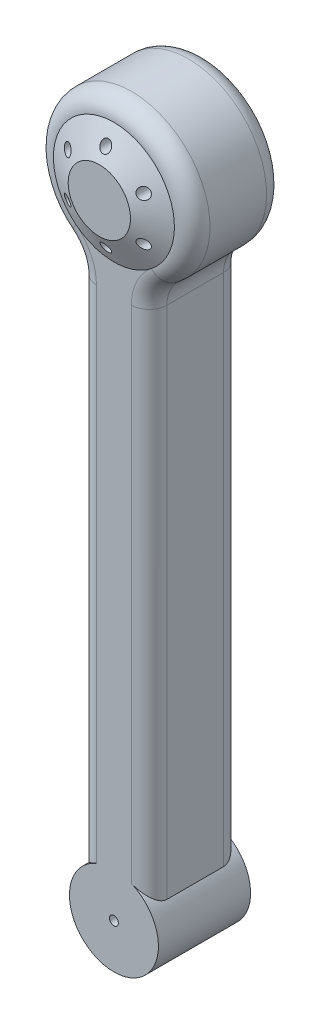
SolidWorks part; units mm, degrees
ref_plane "Ön Düzlem" through (0, 0, 0) normal (0, 0, 1) x (1, 0, 0)
ref_plane "Üst Düzlem" through (0, 0, 0) normal (0, 1, 0) x (1, 0, 0)
ref_plane "Sağ Düzlem" through (0, 0, 0) normal (1, 0, 0) x (0, 0, -1)
sketch "Çizim2" plane through (0, 0, 0) normal (0, 0, 1) x (1, 0, 0)
  line L2 (19.817, 315.2409) -> (19.817, 15.2409)
  line L3 (-19.817, 315.2409) -> (-19.817, 15.2409)
  arc A0 (-19.817, 15.2409) -> (19.817, 15.2409) centre (0, 0) ccw
  arc A1 (-19.817, 315.2409) -> (19.817, 315.2409) centre (0, 354.5256) cw
  point P3 (19.2221, 15.9847)
  point P6 (-19.2221, 15.9847)
  dimension "D1" = 50
  dimension "D4" = 44
  dimension "D2" = 300
  dimension "D3" = 300
extrude "Yükseklik-Ekstrüzyon2" add sketch "Çizim2" along normal blind 51.8
sketch "Çizim3" plane through (0, 0, 51.8) normal (0, 0, 1) x (1, 0, 0)
  circle A0 centre (0, 0) radius 2.5
  dimension "D1" = 5
extrude "Kes-Ekstrüzyon1" cut sketch "Çizim3" against normal blind 20
sketch "Çizim4" plane through (0, 0, 0) normal (0, 0, -1) x (-1, 0, 0)
  circle A0 centre (0, 0) radius 2.5
  dimension "D1" = 5
extrude "Kes-Ekstrüzyon2" cut sketch "Çizim4" against normal blind 20
fillet "Radyus1" radius 20 2 edges at (19.817, 315.2409, 25.9) (-19.817, 315.2409, 25.9)
sketch "Çizim5" plane through (0, 0, 0) normal (0, 0, -1) x (-1, 0, 0)
  line L1 (-21, 333.5256) -> (21, 333.5256)
  line L2 (-21, 333.5256) -> (-21, 375.5256)
  line L3 (-21, 375.5256) -> (21, 375.5256)
  line L4 (21, 333.5256) -> (21, 375.5256)
  line L5 (-21, 333.5256) -> (21, 375.5256) construction
  line L6 (-21, 375.5256) -> (21, 333.5256) construction
  point P0 (0, 354.5256)
  dimension "D1" = 42
  dimension "D2" = 42
extrude "Kes-Ekstrüzyon3" cut sketch "Çizim5" against normal blind 23
ref_plane "Düzlem1" through (0, 0, 65) normal (0, 0, 1) x (1, 0, 0)
ref_plane "Düzlem2" through (0, 0, 55) normal (0, 0, 1) x (1, 0, 0)
fillet "Radyus2" radius 10 10 edges at (-19.817, 159.8303, 0) (-21.8051, 313.1129, 0) (0, 398.5256, 0) (21.8051, 313.1129, 0) (-19.817, 159.8303, 51.8) (-21.8051, 313.1129, 51.8) (21.8051, 313.1129, 51.8) (19.817, 159.8303, 0) (19.817, 159.8303, 51.8) (0, 398.5256, 51.8)
sketch "Çizim6" plane through (0, 0, 51.8) normal (0, 0, 1) x (1, 0, 0)
  circle A0 centre (0, 354.5256) radius 34
ref_plane "Düzlem3" through (0, 0, 60) normal (0, 0, 1) x (1, 0, 0)
sketch "Çizim7" plane through (0, 0, 60) normal (0, 0, 1) x (1, 0, 0)
  circle A0 centre (0, 354.5256) radius 17.5
  dimension "D1" = 35
loft "Loft1" add profiles "Çizim6", "Çizim7"
sketch "Çizim10" plane through (0, 0, 60) normal (0, 0, 1) x (1, 0, 0)
  circle A0 centre (0, 379.1978) radius 3
  circle A1 centre (21.3668, 366.8617) radius 3
  circle A2 centre (21.3668, 342.1895) radius 3
  circle A3 centre (0, 329.8534) radius 3
  circle A4 centre (-21.3668, 342.1895) radius 3
  circle A5 centre (-21.3668, 366.8617) radius 3
  point P15 (0, 354.5256)
  dimension "D1" = 6
extrude "Kes-Ekstrüzyon5" cut sketch "Çizim10" against normal blind 20 and the other way blind 12.5
